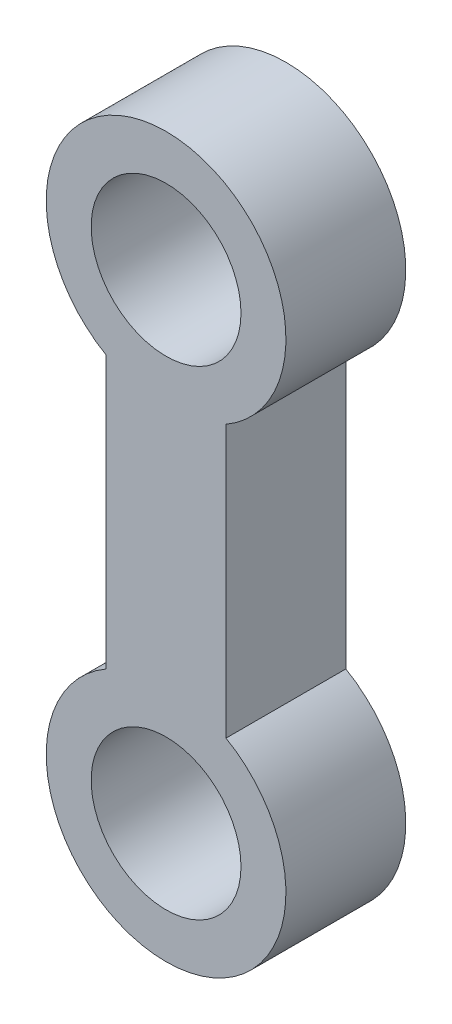
SolidWorks part; units mm, degrees
ref_plane "Front Plane" through (0, 0, 0) normal (0, 0, 1) x (1, 0, 0)
ref_plane "Top Plane" through (0, 0, 0) normal (0, 1, 0) x (1, 0, 0)
ref_plane "Right Plane" through (0, 0, 0) normal (1, 0, 0) x (0, 0, -1)
sketch "Sketch1" plane through (0, 0, 0) normal (0, 0, 1) x (1, 0, 0)
  line L0 (0, 0) -> (0, 51.7958) construction
  line L1 (-5, 0) -> (5, 0)
  line L2 (-5, 0) -> (-5, 40)
  line L3 (-5, 40) -> (5, 40)
  line L4 (5, 0) -> (5, 40)
  circle A0 centre (0, 0) radius 10
  circle A1 centre (0, 40) radius 10
  point P9 (0, 0)
  dimension "D2" = 20
  dimension "D1" = 40
  dimension "D3" = 10
extrude "Boss-Extrude1" add sketch "Sketch1" along normal blind 10 contours L0 L3 L4 A1 | L3 L0 A1 L2 | A1 L0 L3 L2 | L0 A1 L4 L3 | L0 A0 L4 A1 | A0 L0 A1 L2 | L1 L0 A0 L2 | L0 L1 L4 A0 | L2 A0 L4 L1
sketch "Sketch2" plane through (0, 0, 10) normal (0, 0, 1) x (1, 0, 0)
  circle A0 centre (0, 40) radius 6.25
  circle A1 centre (0, 0) radius 6.25
  dimension "D1" = 12.5
extrude "Cut-Extrude1" cut sketch "Sketch2" against normal through all contours A0 | A1
